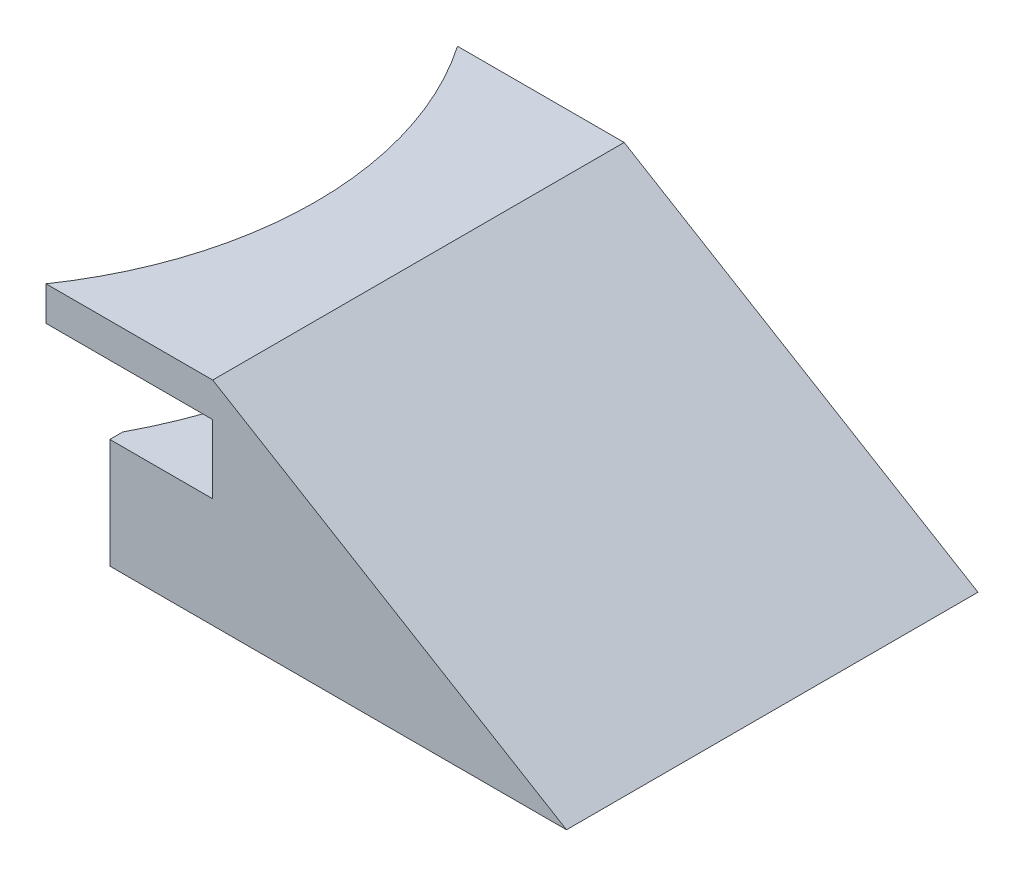
SolidWorks part; units mm, degrees
material "ABS generico"
ref_plane "Piano frontale" through (0, 0, 0) normal (0, 0, 1) x (1, 0, 0)
ref_plane "Piano superiore" through (0, 0, 0) normal (0, 1, 0) x (1, 0, 0)
ref_plane "Piano destro" through (0, 0, 0) normal (1, 0, 0) x (0, 0, -1)
sketch "Schizzo1" plane through (0, 0, 0) normal (0, 0, 1) x (1, 0, 0)
  line L0 (-65, 26) -> (0, 26)
  line L1 (0, 26) -> (0, 16)
  line L2 (0, 16) -> (-15, 16)
  line L3 (-15, 16) -> (-15, 0)
  line L4 (-15, 0) -> (51.5927, 0)
  line L5 (51.5927, 0) -> (0, 31)
  line L6 (0, 31) -> (-65, 31)
  line L7 (-65, 31) -> (-65, 26)
  line L8 (0, 26) -> (0, 31) construction
  dimension "D1" = 10
  dimension "D2" = 5
  dimension "D3" = 16
  dimension "D5" = 50
  dimension "D6" = 15
  dimension "D7" = 31
extrude "Estrusione-Estrusione1" add sketch "Schizzo1" along normal blind 60
sketch "Schizzo2" plane through (0, 31, 0) normal (0, 1, 0) x (1, 0, 0)
  line L0 (-15, -60) -> (-15, 0) construction
  line L1 (0, -60) -> (-65, -60) construction
  line L2 (0, 0) -> (-65, 0) construction
  line L3 (-68, -30) -> (-15, -30) construction
  line L4 (0, -60) -> (0, 0) construction
  circle A0 centre (-68, -30) radius 53
  point P11 (-15, -30)
  dimension "D1" = 106
  dimension "D2" = 15
extrude "Taglio-Estrusione1" cut sketch "Schizzo2" against normal blind 60
sketch "Schizzo3" plane through (0, 0, 0) normal (0, -1, 0) x (1, 0, 0)
  circle A0 centre (-68, 30) radius 60
  dimension "D1" = 120
extrude "Taglio-Estrusione2" cut sketch "Schizzo3" against normal blind 21
